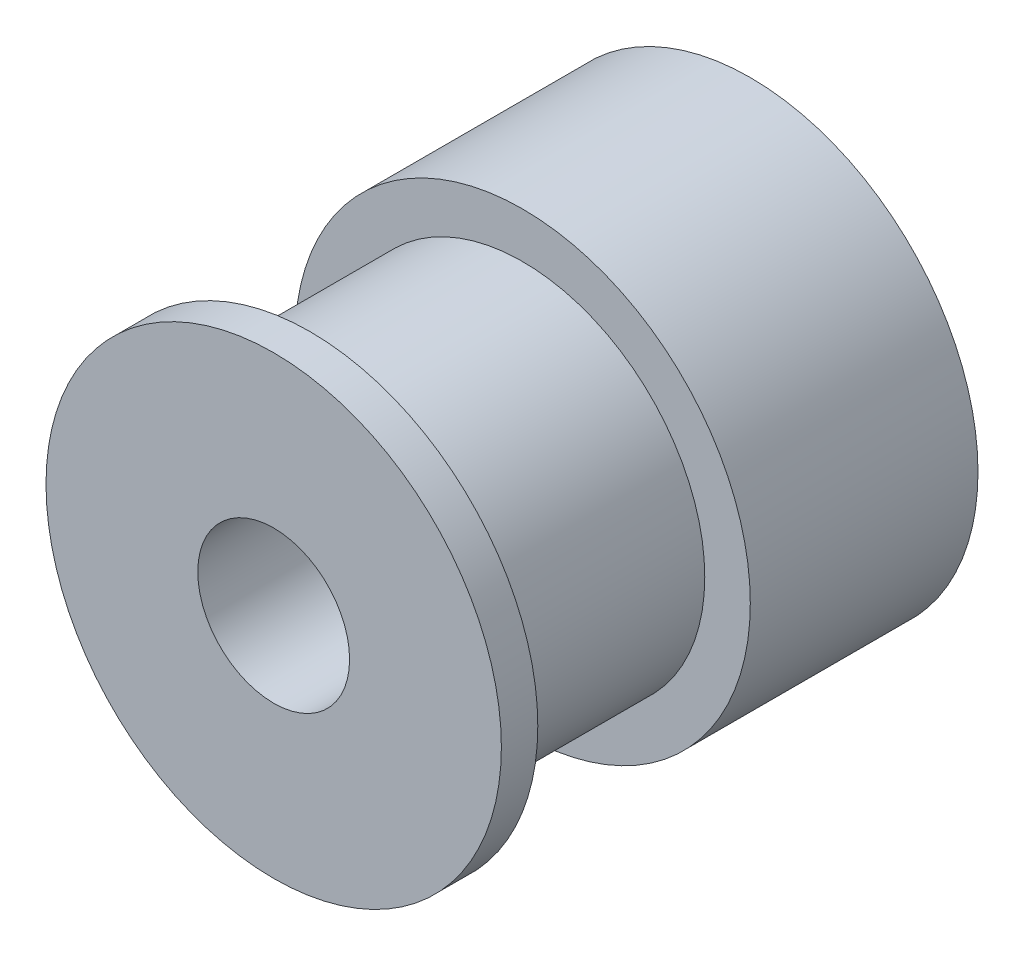
SolidWorks part; units mm, degrees
ref_plane "Plan de face" through (0, 0, 0) normal (0, 0, 1) x (1, 0, 0)
ref_plane "Plan de dessus" through (0, 0, 0) normal (0, 1, 0) x (1, 0, 0)
ref_plane "Plan de droite" through (0, 0, 0) normal (1, 0, 0) x (0, 0, -1)
sketch "Esquisse1" plane through (0, 0, 0) normal (0, 0, 1) x (1, 0, 0)
  circle A0 centre (0, 0) radius 7.5
  dimension "D1" = 15
extrude "Boss.-Extru.1" add sketch "Esquisse1" along normal blind 7.5
sketch "Esquisse2" plane through (0, 0, 7.5) normal (0, 0, 1) x (1, 0, 0)
  circle A0 centre (0, 0) radius 6
  dimension "D1" = 12
extrude "Boss.-Extru.2" add sketch "Esquisse2" along normal blind 7
sketch "Esquisse3" plane through (0, 0, 14.5) normal (0, 0, 1) x (1, 0, 0)
  circle A0 centre (0, 0) radius 7.5
  dimension "D1" = 15
extrude "Boss.-Extru.3" add sketch "Esquisse3" along normal blind 1.2
sketch "Esquisse4" plane through (0, 0, 0) normal (0, 0, -1) x (-1, 0, 0)
  circle A0 centre (0, 0) radius 2.5
  dimension "D1" = 5
extrude "Enlèv. mat.-Extru.1" cut sketch "Esquisse4" against normal blind 30
